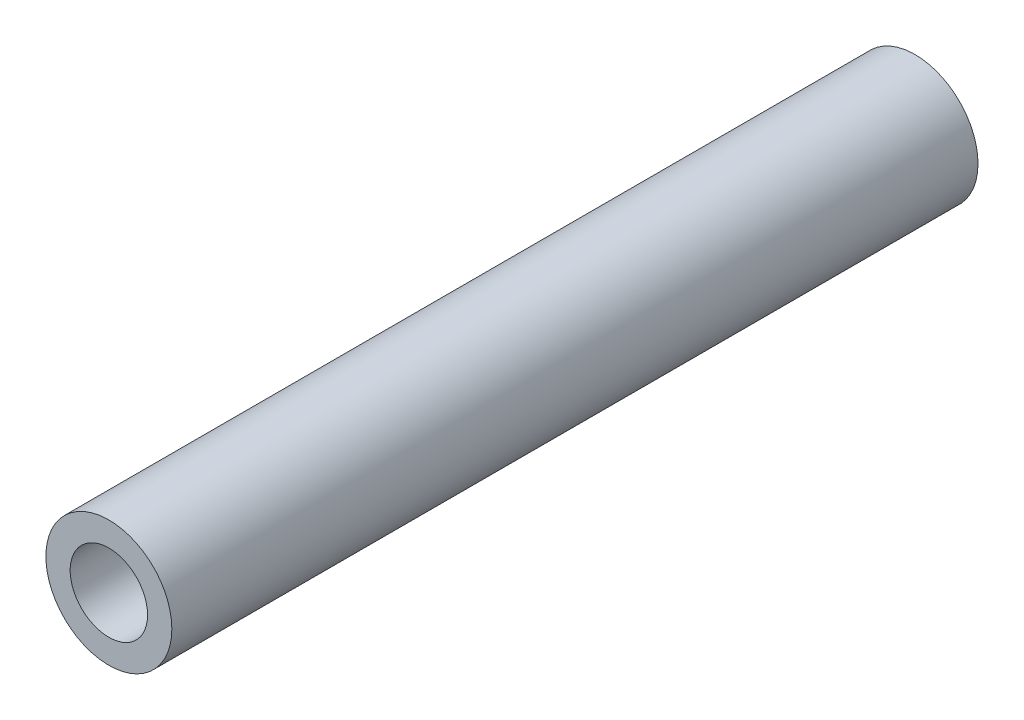
SolidWorks part; units mm, degrees
ref_plane "Front Plane" through (0, 0, 0) normal (0, 0, 1) x (1, 0, 0)
ref_plane "Top Plane" through (0, 0, 0) normal (0, 1, 0) x (1, 0, 0)
ref_plane "Right Plane" through (0, 0, 0) normal (1, 0, 0) x (0, 0, -1)
sketch "Sketch1" plane through (0, 0, 0) normal (0, 0, 1) x (1, 0, 0)
  circle A0 centre (0, 0) radius 3.9688
  circle A1 centre (0, 0) radius 2.4384
  dimension "OD" = 7.9375
  dimension "ID" = 4.8768
extrude "Extrude1" add sketch "Sketch1" along normal mid plane 50.8
sketch "Sketch2" plane through (0, 0, 0) normal (1, 0, 0) x (0, 0, -1)
  line L0 (-25.4, -2.4384) -> (25.4, -2.4384) construction
  line L3 (25.4, 2.4384) -> (-25.4, 2.4384) construction
  line L5 (-25.4, -2.4384) -> (25.4, -2.4384)
  line L6 (25.4, 2.4384) -> (-25.4, 2.4384)
sketch "Sketch4" plane through (0, 0, 25.4) normal (0, 0, 1) x (1, 0, 0)
  line L0 (0, 0) -> (-1.7242, 1.7242)
  line L1 (0, -2.1828) -> (0, 2.1828) construction
  circle A0 centre (0, 0) radius 2.4384 construction
  dimension "D1" = 45
